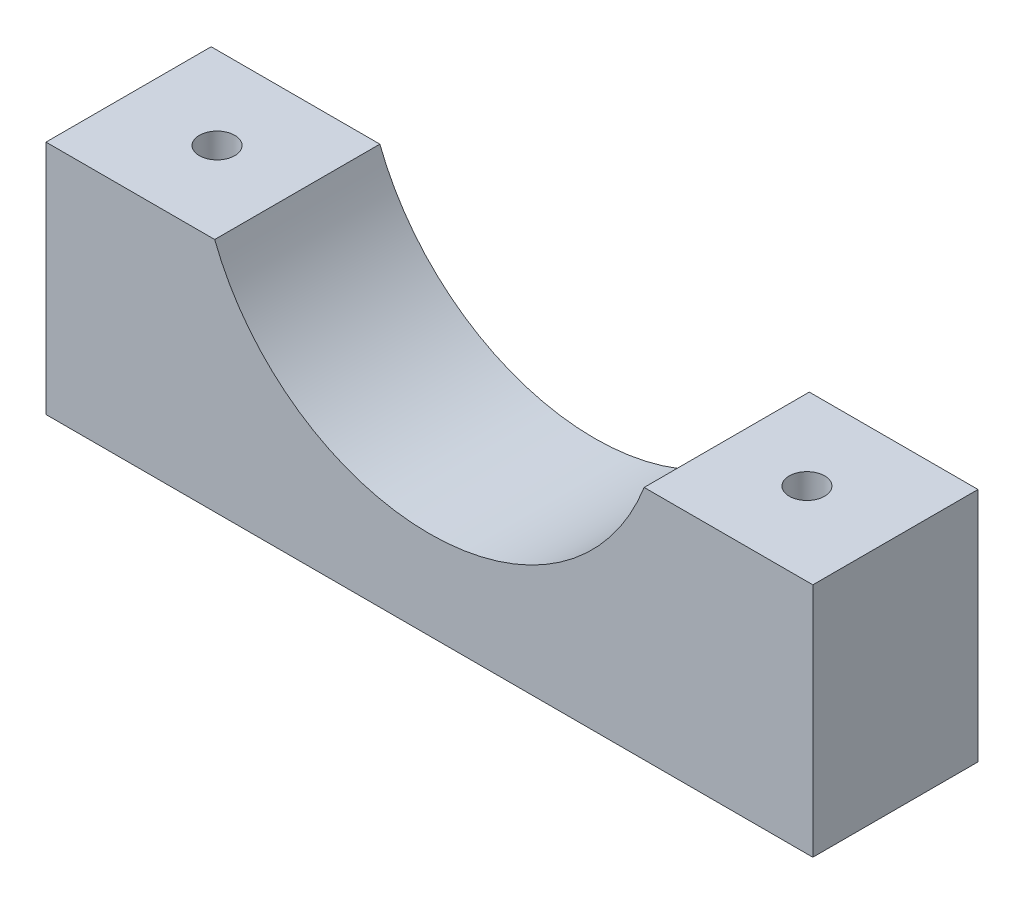
SolidWorks part; units mm, degrees
ref_plane "Front Plane" through (0, 0, 0) normal (0, 0, 1) x (1, 0, 0)
ref_plane "Top Plane" through (0, 0, 0) normal (0, 1, 0) x (1, 0, 0)
ref_plane "Right Plane" through (0, 0, 0) normal (1, 0, 0) x (0, 0, -1)
sketch "Sketch1" plane through (0, 0, 0) normal (0, 1, 0) x (1, 0, 0)
  line L1 (0, 0) -> (65, 0)
  line L2 (0, 0) -> (0, 14)
  line L3 (0, 14) -> (65, 14)
  line L4 (65, 0) -> (65, 14)
  dimension "D1" = 65
  dimension "D2" = 14
extrude "Boss-Extrude1" add sketch "Sketch1" along normal blind 20
sketch "Sketch2" plane through (0, 0, 0) normal (0, 0, 1) x (1, 0, 0)
  line L0 (0, 0) -> (65, 0) construction
  line L1 (0, 0) -> (65, 0) construction
  line L2 (0, 20) -> (0, 0) construction
  circle A0 centre (32.5, 27) radius 19.5
  dimension "D1" = 39
  dimension "D2" = 27
  dimension "D3" = 32.5
extrude "Cut-Extrude1" cut sketch "Sketch2" against normal up to surface (14 mm away) up to face at (32.5, 10, -14)
hole_wizard "Hole1" positions "Sketch3" profile "Sketch4" legacy
sketch "Sketch3" plane through (0, 0, 0) normal (0, -1, 0) x (-1, 0, 0)
  line L0 (-65, 0) -> (-65, 14) construction
  line L1 (0, 14) -> (0, 0) construction
  line L2 (0, 0) -> (-65, 0) construction
  point P0 (-57.5, 7)
  point P3 (-7.5, 7)
  dimension "D1" = 7.5
  dimension "D2" = 7.5
  dimension "D3" = 7
  dimension "D4" = 7
sketch "Sketch4" plane through (57.5, 0, -7) normal (1, 0, 0) x (0, 0, -1)
  line L0 (0, 0) -> (0, 20)
  line L1 (0, 20) -> (1.5, 20)
  line L2 (1.5, 20) -> (1.5, 0)
  line L3 (1.5, 0) -> (0, 0)
  line L4 (0, 110) -> (0, -10) construction
  dimension "Diameter" = 3
  dimension "Depth" = 20
